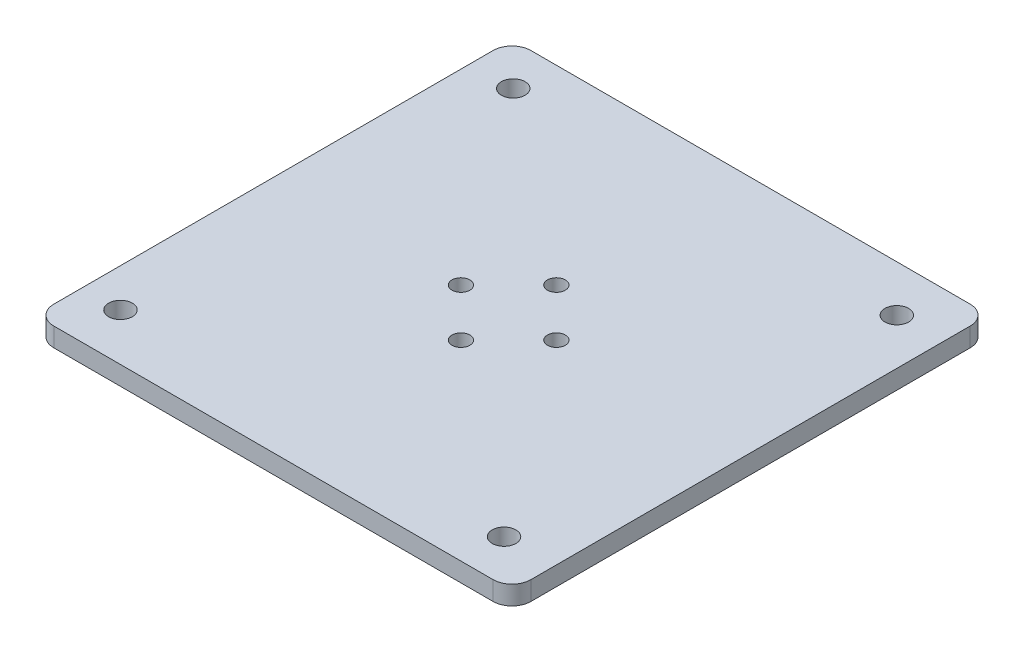
SolidWorks part; units mm, degrees
material "6061 Alloy"
ref_plane "Front Plane" through (0, 0, 0) normal (0, 0, 1) x (1, 0, 0)
ref_plane "Top Plane" through (0, 0, 0) normal (0, 1, 0) x (1, 0, 0)
ref_plane "Right Plane" through (0, 0, 0) normal (1, 0, 0) x (0, 0, -1)
sketch "Sketch1" plane through (0, 0, 0) normal (0, 1, 0) x (1, 0, 0)
  line L1 (40, -40) -> (-40, -40)
  line L2 (40, -40) -> (40, 40)
  line L3 (40, 40) -> (-40, 40)
  line L4 (-40, -40) -> (-40, 40)
  line L5 (40, -40) -> (-40, 40) construction
  line L6 (40, 40) -> (-40, -40) construction
  point P0 (0, 0)
  dimension "D1" = 80
  dimension "D2" = 80
extrude "Boss-Extrude1" add sketch "Sketch1" along normal blind 3.175
sketch "Sketch16" plane through (0, 3.175, 0) normal (0, 1, 0) x (1, 0, 0)
  line L0 (50, 50) -> (-50, -50) construction
  line L1 (40, 40) -> (-40, -40) construction
  circle A0 centre (-32.8008, 33.0058) radius 1.9844
  circle A1 centre (32.2821, 32.2365) radius 1.9844
  circle A2 centre (31.5128, -32.8465) radius 1.9844
  circle A3 centre (-33.5701, -32.0772) radius 1.9844
  point P14 (0, 0)
  point P15 (0, 0)
  dimension "D2" = 46.5323
  dimension "D3" = 1.0557
  dimension "D4" = 45.5089
  dimension "D5" = 65.0875
  dimension "D6" = 65.0875
  dimension "D7" = 65.0875
  dimension "D1" = 0.0646
extrude "Cut-Extrude8" cut sketch "Sketch16" against normal blind 10
ref_plane "Plane1" through (0, 3.175, 0) normal (0, 1, 0) x (1, 0, 0)
fillet "Fillet1" radius 3.175 4 edges at (-40, 1.5875, -40) (40, 1.5875, -40) (40, 1.5875, 40) (-40, 1.5875, 40)
sketch "Sketch21" plane through (0, 0, 0) normal (0, -1, 0) x (1, 0, 0)
  line L0 (-36.825, 40) -> (36.825, 40) construction
  line L3 (-40, -36.825) -> (-40, 36.825) construction
  circle A0 centre (-0.64, -0.08) radius 11
  circle A1 centre (-0.64, -0.08) radius 2
  circle A2 centre (-0.64, 7.92) radius 1.5
  circle A3 centre (7.36, -0.08) radius 1.5
  circle A4 centre (-0.64, -0.08) radius 2
  circle A5 centre (-0.64, -8.08) radius 1.5
  circle A6 centre (-0.64, -0.08) radius 2
  circle A7 centre (-8.64, -0.08) radius 1.5
  circle A8 centre (-0.64, -0.08) radius 2
  point P24 (-0.64, -0.08)
  dimension "D2" = 22
  dimension "D1" = 4
  dimension "D3" = 3
  dimension "D4" = 8
  dimension "D5" = 4
  dimension "D6" = 40.08
  dimension "D7" = 39.36
ref_plane "Plane2" through (0, 0, 0) normal (0, -1, 0) x (-1, 0, 0)
sketch "Sketch24" [suppressed] plane through (0, 0, 0) normal (0, -1, 0) x (-1, 0, 0)
  line L0 (-40, -36.825) -> (-40, 36.825) construction
  line L1 (-36.825, 40) -> (36.825, 40) construction
  point P0 (-25.9175, 6.35)
  point P1 (-25.9175, -6.35)
  point P2 (25.9175, 6.35)
  point P3 (25.9175, -6.35)
  dimension "D1" = 51.835
  dimension "D2" = 12.7
  dimension "D3" = 14.0825
  dimension "D4" = 33.65
hole_wizard "M4x0.7 Tapped Hole1" [suppressed] positions "Sketch25" profile "Sketch26" tap size "M4x0.7" standard "ANSI Metric"
sketch "Sketch25" [suppressed] plane through (0, 0, 0) normal (0, -1, 0) x (-1, 0, 0)
  point P0 (-25.9175, 6.35)
  point P3 (-25.9175, -6.35)
  point P6 (25.9175, 6.35)
  point P9 (25.9175, -6.35)
sketch "Sketch26" plane through (25.9175, 0, -6.35) normal (1, 0, 0) x (0, 0, -1)
  line L0 (0, 0) -> (0, 3.175)
  line L1 (0, 3.175) -> (1.65, 3.175)
  line L2 (1.65, 3.175) -> (1.65, 0)
  line L5 (1.65, 0) -> (0, 0)
  line L11 (0, -6.35) -> (0, 107.95) construction
  dimension "Thru Tap Drill Dia." = 3.3
  dimension "Thru Tap Drill Depth" = 3.175
extrude "Cut-Extrude9" cut sketch "Sketch21" against normal blind 10 contours A5 | A7 | A2 | A3
